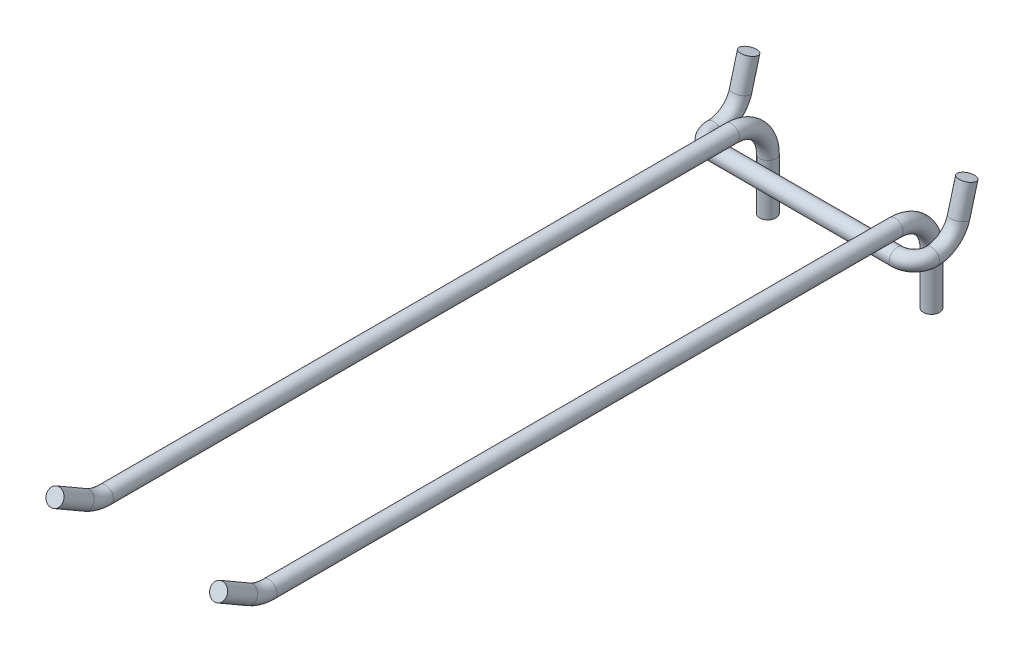
SolidWorks part; units mm, degrees
ref_plane "Front Plane" through (0, 0, 0) normal (0, 0, 1) x (1, 0, 0)
ref_plane "Top Plane" through (0, 0, 0) normal (0, 1, 0) x (1, 0, 0)
ref_plane "Right Plane" through (0, 0, 0) normal (1, 0, 0) x (0, 0, -1)
sketch "Sketch1" plane through (0, 0, 0) normal (1, 0, 0) x (0, 0, -1)
  line L0 (-72.9107, 0) -> (72.9107, 0)
  line L1 (-78.6003, 1.5245) -> (-85.6107, 5.572)
  line L2 (0, 3.7592) -> (-72.9107, 3.7592) construction
  line L3 (79.4893, -6.5786) -> (79.4893, -18.5738)
  line L4 (71.0311, -1.8796) -> (75.0171, -1.8796)
  line L5 (81.3715, 2.9963) -> (83.2485, 10.0012)
  line L6 (83.2485, -6.5786) -> (83.2485, -18.5737)
  line L7 (79.4893, -18.5738) -> (83.2485, -18.5737) construction
  line L8 (-85.6107, -18.5738) -> (79.4893, -18.5738) construction
  arc A0 (-72.9107, 0) -> (-78.6003, 1.5245) centre (-72.9107, 11.3792) cw
  circle A1 centre (0, 1.8796) radius 1.8796
  arc A2 (-72.9107, 3.7592) -> (-72.9107, 18.9992) centre (-72.9107, 11.3792) cw construction
  arc A3 (72.9107, 0) -> (79.4893, -6.5786) centre (72.9107, -6.5786) cw
  circle A4 centre (71.0311, -1.8796) radius 1.8796
  arc A5 (75.0171, -1.8796) -> (81.3715, 2.9963) centre (75.0171, 4.699) ccw
  circle A6 centre (81.3689, -6.5786) radius 1.8796
  point P26 (0, -18.5738)
  point P34 (72.9107, -1.8796)
  dimension "Wire Diameter" = 3.7592
  dimension "D4" = 7.62
  dimension "D8" = 6.5786
  dimension "D1" = 30
  dimension "A" = 12.7
  dimension "D6" = 105
  dimension "Height" = 28.575
  dimension "D7" = 18.5738
  dimension "P" = 152.4
sketch "Sketch2" plane through (0, 0, 0) normal (0, 1, 0) x (1, 0, 0)
  line L0 (-25.4, 83.2485) -> (25.4, 83.2485)
  line L1 (-19.05, 0) -> (19.05, 0)
  point P5 (-20.9296, 0)
  dimension "Center to Center" = 50.8
  dimension "C" = 38.1
  dimension "D2" = 1.8796
ref_plane "Plane1" through (0, -18.5738, 0) normal (0, -1, 0) x (0, 0, -1)
sketch "Sketch11" plane through (0, -18.5738, 0) normal (0, -1, 0) x (0, 0, -1)
  line L0 (79.4893, 0) -> (83.2485, 0) construction
  circle A0 centre (81.3689, 0) radius 1.8796
sketch "Sketch3" plane through (0, 0, 0) normal (1, 0, 0) x (0, 0, -1)
  line L0 (79.4893, -6.5786) -> (79.4893, -18.5738) construction
  line L1 (-72.9107, 0) -> (72.9107, 0) construction
  line L2 (-78.6003, 1.5245) -> (-85.6107, 5.572) construction
  line L3 (79.4893, -6.5786) -> (79.4893, -18.5738)
  line L4 (-72.9107, 0) -> (72.9107, 0)
  line L5 (-78.6003, 1.5245) -> (-85.6107, 5.572)
  arc A0 (79.4893, -6.5786) -> (72.9107, 0) centre (72.9107, -6.5786) ccw construction
  arc A1 (-78.6003, 1.5245) -> (-72.9107, 0) centre (-72.9107, 11.3792) ccw construction
  arc A2 (79.4893, -6.5786) -> (72.9107, 0) centre (72.9107, -6.5786) ccw
  arc A3 (-78.6003, 1.5245) -> (-72.9107, 0) centre (-72.9107, 11.3792) ccw
sweep "Sweep1" add profiles "Sketch11" path "Sketch3"
sketch "Sketch4" plane through (0, 0, 0) normal (1, 0, 0) x (0, 0, -1)
  line L0 (81.3715, 2.9963) -> (83.2485, 10.0012) construction
  line L1 (71.0311, -1.8796) -> (75.0171, -1.8796) construction
  line L2 (81.3715, 2.9963) -> (83.2485, 10.0012)
  line L3 (71.0311, -1.8796) -> (75.0171, -1.8796)
  arc A0 (75.0171, -1.8796) -> (81.3715, 2.9963) centre (75.0171, 4.699) ccw construction
  arc A1 (75.0171, -1.8796) -> (81.3715, 2.9963) centre (75.0171, 4.699) ccw
surface "Surface-Extrude1" sketch "Sketch4" parameters "D1"=50.8
ref_plane "Plane2" through (0, 10.0012, 0) normal (0, 1, 0) x (1, 0, 0)
sketch "Sketch6" plane through (0, 10.0012, 0) normal (0, 1, 0) x (1, 0, 0)
  line L0 (-25.4, 83.2485) -> (-25.4, 75.0171)
  line L1 (25.4, 71.0311) -> (-25.4, 71.0311) construction
  line L2 (-21.414, 71.0311) -> (21.414, 71.0311)
  line L3 (0, 69.1515) -> (0, 72.9107) construction
  line L4 (0, 71.0311) -> (0, 83.2485) construction
  line L5 (25.4, 83.2485) -> (25.4, 75.0171)
  arc A0 (-25.4, 75.0171) -> (-21.414, 71.0311) centre (-21.414, 75.0171) ccw
  arc A1 (25.4, 75.0171) -> (21.414, 71.0311) centre (21.414, 75.0171) cw
curve "Curve2"
sweep "Sweep2" add path "Curve2" circular profile diameter 3.7592 parameters "D3"=3.7592
delete or keep bodies "Body-Delete/Keep 1" type delete bodies bodies 135
pattern_linear "LPattern1" count 2 spacing 19.05 along (-1, 0, 0) of bodies 134
mirror "Mirror1" about plane through (0, 0, 0) normal (1, 0, 0) of bodies 139
delete or keep bodies "Body-Delete/Keep 2" type delete bodies bodies 134
equation "\"D7@Sketch1\" = \"Height@Sketch1\" * 0.65"
equation "\"D8@Sketch1\" = \"Wire Diameter@Sketch1\" * 1.75"
equation "\"D1@Surface-Extrude1\"=\"center to center@sketch2\""
equation "\"D2@Sketch2\"=\"wire diameter@sketch1\"/2"
equation "\"D3@Sweep2\"=\"wire diameter@sketch1\""
